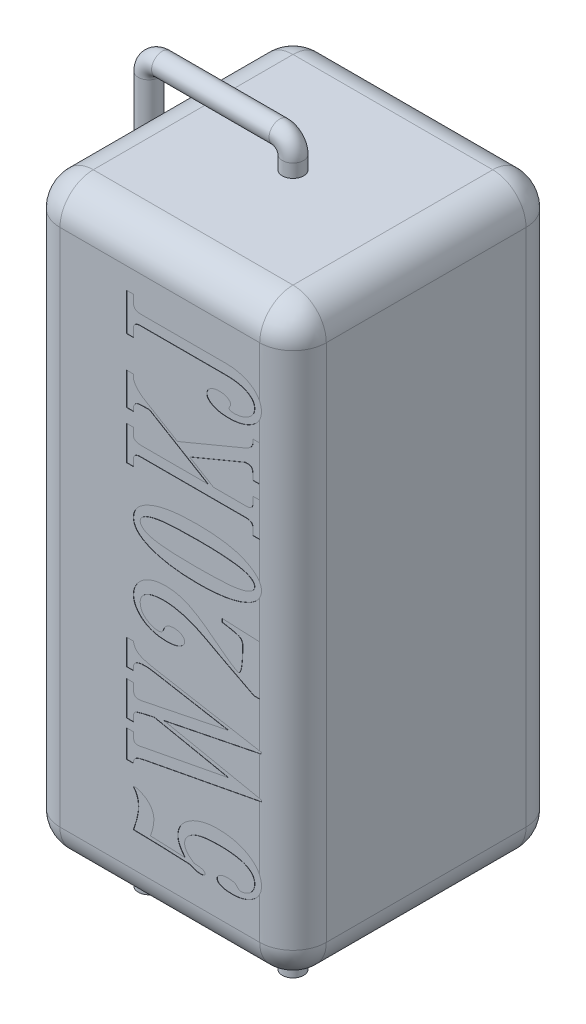
SolidWorks part; units mm, degrees
ref_plane "Front Plane" through (0, 0, 0) normal (0, 0, 1) x (1, 0, 0)
ref_plane "Top Plane" through (0, 0, 0) normal (0, 1, 0) x (1, 0, 0)
ref_plane "Right Plane" through (0, 0, 0) normal (1, 0, 0) x (0, 0, -1)
sketch "Sketch1" plane through (0, 0, 0) normal (0, 1, 0) x (1, 0, 0)
  line L1 (-3.75, 5) -> (3.75, 5)
  line L2 (-5, 3.75) -> (-5, -3.75)
  line L3 (-3.75, -5) -> (3.75, -5)
  line L4 (5, 3.75) -> (5, -3.75)
  line L5 (-5, 5) -> (5, -5) construction
  line L6 (-5, -5) -> (5, 5) construction
  arc A0 (3.75, 5) -> (5, 3.75) centre (3.75, 3.75) cw
  arc A1 (5, -3.75) -> (3.75, -5) centre (3.75, -3.75) cw
  arc A2 (-3.75, -5) -> (-5, -3.75) centre (-3.75, -3.75) cw
  arc A3 (-5, 3.75) -> (-3.75, 5) centre (-3.75, 3.75) cw
  point P0 (0, 0)
  dimension "D2" = 1.25
  dimension "D1" = 10
extrude "Boss-Extrude1" add sketch "Sketch1" along normal blind 22
fillet "Fillet1" radius 1.25 16 edges at (0, 0, -5) (-4.6339, 0, -4.6339) (-5, 0, 0) (-4.6339, 0, 4.6339) (0, 0, 5) (4.6339, 0, 4.6339) (5, 0, 0) (4.6339, 0, -4.6339) (5, 22, 0) (4.6339, 22, 4.6339) (0, 22, 5) (-4.6339, 22, 4.6339) (-5, 22, 0) (-4.6339, 22, -4.6339) (0, 22, -5) (4.6339, 22, -4.6339)
sketch "Sketch2" plane through (0, 0, 0) normal (0, -1, 0) x (1, 0, 0)
  circle A0 centre (0, 0) radius 0.4
  dimension "D1" = 0.8
extrude "Boss-Extrude2" add sketch "Sketch2" along normal blind 4
sketch "Sketch3" plane through (0, 0, 0) normal (0, 0, 1) x (1, 0, 0)
  line L0 (0, 22) -> (0, 22.5)
  line L1 (-3.75, 22) -> (3.75, 22) construction
  line L2 (-0.5, 23) -> (-4.91, 23)
  line L3 (-5.41, 22.5) -> (-5.41, -4)
  line L4 (0, -4) -> (-22.4023, -4) construction
  line L5 (-0.4, -4) -> (0.4, -4) construction
  line L6 (0, 25.9094) -> (0, -4) construction
  arc A0 (-0.5, 23) -> (0, 22.5) centre (-0.5, 22.5) cw
  arc A1 (-5.41, 22.5) -> (-4.91, 23) centre (-4.91, 22.5) cw
  point P11 (0, -4.2475)
  point P13 (0, 22.5706)
  point P16 (0, 23)
  dimension "D3" = 0.5
  dimension "D4" = 0.5
  dimension "D1" = 5.41
  dimension "D2" = 1
sweep "Sweep2" add path "Sketch3" circular profile diameter 0.8 parameters "D3"=0.8
sketch "Sketch28" plane through (0, 0, 5) normal (0, 0, 1) x (1, 0, 0)
  line L0 (3.75, 1.25) -> (3.75, 20.75) construction
  text T0 "5W20KJ" font "Century" height 5
extrude "Cut-Extrude1" cut sketch "Sketch28" against normal blind 0.01
